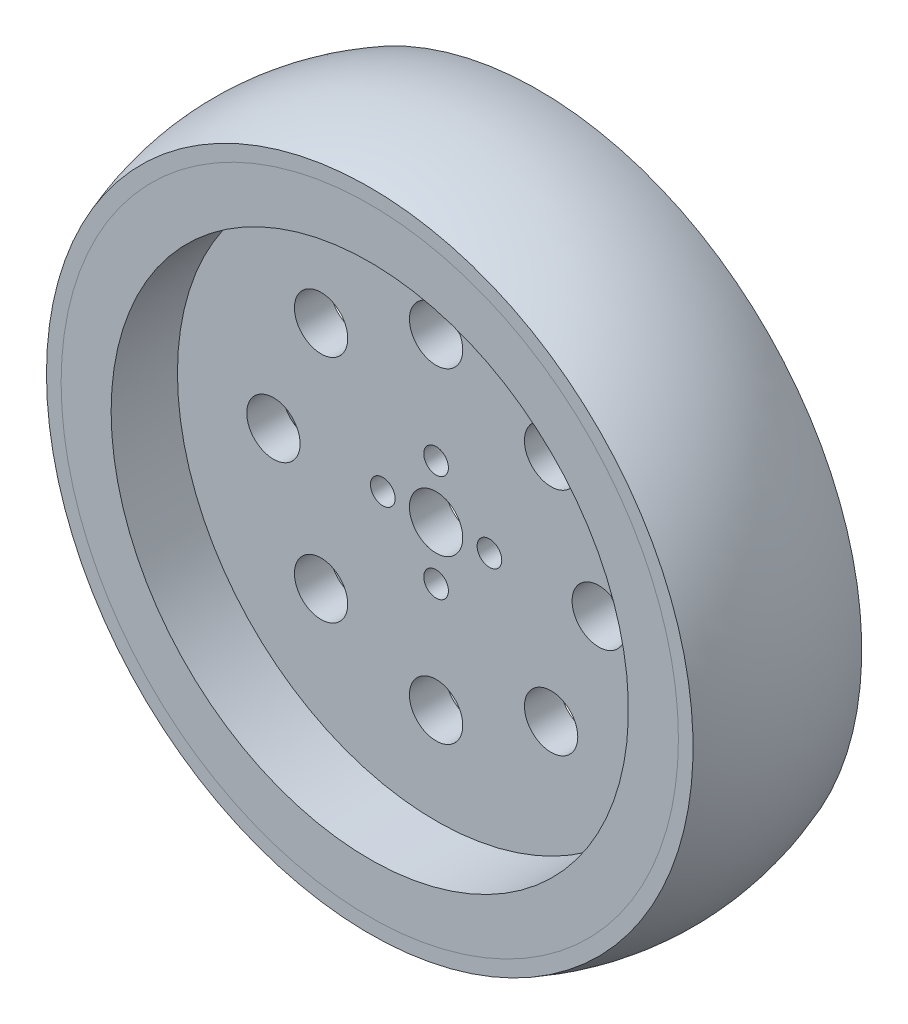
SolidWorks part; units mm, degrees
other "Defeature"
material "Nylon 6/10"
ref_plane "Front Plane" through (0, 0, 0) normal (0, 0, 1) x (1, 0, 0)
ref_plane "Top Plane" through (0, 0, 0) normal (0, 1, 0) x (1, 0, 0)
ref_plane "Right Plane" through (0, 0, 0) normal (1, 0, 0) x (0, 0, -1)
sketch "Sketch1" plane through (0, 0, 0) normal (0, 1, 0) x (1, 0, 0)
  line L0 (0, 12.65) -> (0, -12.65) construction
  line L1 (4, -2.7) -> (38.8, -2.7)
  line L2 (38.8, -2.7) -> (38.8, -12.65)
  line L3 (38.8, -12.65) -> (46.3, -12.65)
  line L4 (46.3, -12.65) -> (46.3, -10.65)
  line L5 (46.3, -10.65) -> (44, -10.65)
  line L6 (44, -10.65) -> (44, 10.65)
  line L7 (44, 10.65) -> (46.3, 10.65)
  line L8 (46.3, 10.65) -> (46.3, 12.65)
  line L9 (46.3, 12.65) -> (38.8, 12.65)
  line L10 (4, 2.7) -> (4, -2.7)
  line L11 (38.8, 12.65) -> (38.8, 2.7)
  line L12 (38.8, 2.7) -> (4, 2.7)
  point P3 (0, 0)
  point P13 (44, 0)
  point P15 (4, 0)
  dimension "D1" = 8
  dimension "D2" = 92.6
  dimension "D3" = 7.5
  dimension "D4" = 2.3
  dimension "D5" = 5.4
  dimension "D6" = 25.3
  dimension "D7" = 2
revolve "Revolve1" add sketch "Sketch1" angle 360 about L0
sketch "Sketch2" plane through (0, 0, 0) normal (0, 1, 0) x (1, 0, 0)
  line L0 (44, -10.65) -> (44, 10.65) construction
  line L1 (-46.3, 10.65) -> (46.3, 10.65) construction
  line L2 (46.3, -10.65) -> (-46.3, -10.65) construction
  line L3 (46.3, -12.65) -> (46.3, -10.65) construction
  line L4 (46.3, 10.65) -> (46.3, 12.65) construction
  line L5 (44, -10.65) -> (44, 10.65)
  line L6 (44, 10.65) -> (46.3, 10.65)
  line L7 (46.3, -10.65) -> (44, -10.65)
  line L8 (46.3, -12.65) -> (46.3, -10.65)
  line L9 (46.3, 10.65) -> (46.3, 12.65)
  line L10 (0, 12.65) -> (0, -12.65) construction
  line L11 (46.3, 12.65) -> (-46.3, 12.65) construction
  line L12 (-46.3, -12.65) -> (46.3, -12.65) construction
  line L13 (46.3, -12.65) -> (48.5, -12.65)
  line L14 (46.3, 12.65) -> (48.5, 12.65)
  arc A0 (48.5, 12.65) -> (48.5, -12.65) centre (14.8625, 0) cw
  point P17 (50.8, 0)
  dimension "D1" = 101.6
  dimension "D2" = 2.2
revolve "Revolve2" add sketch "Sketch2" angle 360 about L10
sketch "Sketch3" plane through (0, 0, 0) normal (0, 0, 1) x (1, 0, 0)
  line L0 (-17.2534, 17.2534) -> (17.2534, -17.2534) construction
  line L1 (17.2534, 17.2534) -> (-17.2534, -17.2534) construction
  line L2 (0, 0) -> (0, -24.4) construction
  circle A0 centre (0, 8) radius 1.85
  circle A1 centre (8, 0) radius 1.85
  circle A2 centre (0, -8) radius 1.85
  circle A3 centre (-8, 0) radius 1.85
  circle A4 centre (0, 0) radius 8 construction
  circle A5 centre (0, 0) radius 24.4 construction
  circle A6 centre (0, 24.4) radius 4
  circle A7 centre (17.2534, 17.2534) radius 4
  circle A8 centre (24.4, 0) radius 4
  circle A9 centre (17.2534, -17.2534) radius 4
  circle A10 centre (0, -24.4) radius 4
  circle A11 centre (-17.2534, -17.2534) radius 4
  circle A12 centre (-24.4, 0) radius 4
  circle A13 centre (-17.2534, 17.2534) radius 4
  circle A14 centre (0, 0) radius 4 construction
  point P28 (0, 20.4)
  point P29 (0, 4)
  dimension "D1" = 8
  dimension "D2" = 3.7
  dimension "D3" = 16
  dimension "D4" = 45
  dimension "D5" = 16.4
extrude "Cut-Extrude1" cut sketch "Sketch3" against normal through all both and the other way through all
